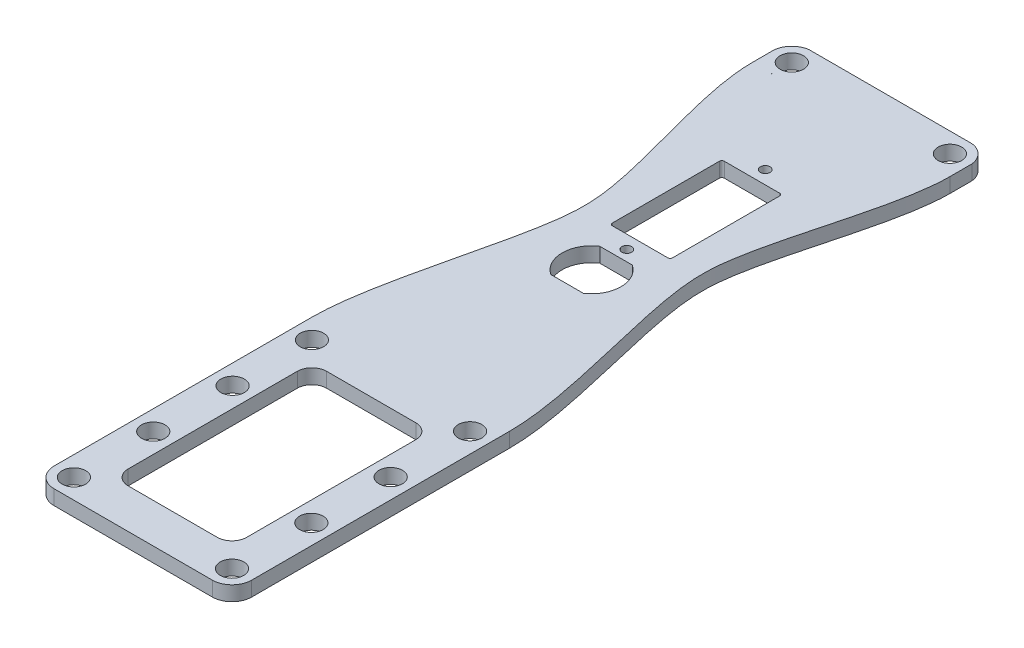
SolidWorks part; units mm, degrees
ref_plane "Front Plane" through (0, 0, 0) normal (0, 0, 1) x (1, 0, 0)
ref_plane "Top Plane" through (0, 0, 0) normal (0, 1, 0) x (1, 0, 0)
ref_plane "Right Plane" through (0, 0, 0) normal (1, 0, 0) x (0, 0, -1)
sketch "Sketch2" plane through (0, 0, 0) normal (0, 1, 0) x (1, 0, 0)
  line L4 (0.3089, 36.1371) -> (40.6689, 36.1371)
  line L5 (0.3089, 36.1371) -> (0.3089, 28.0671)
  line L6 (0.3832, -61.9329) -> (40.7432, -61.9329)
  line L11 (0.3832, -61.9329) -> (40.7432, -61.9329)
  line L12 (0.3832, -61.9329) -> (0.3832, -118.6029)
  line L13 (0.3832, -118.6029) -> (40.7432, -118.6029)
  line L14 (40.7432, -61.9329) -> (40.7432, -118.6029)
  line L15 (0.3832, -61.9329) -> (0.3832, -70.0029)
  line L17 (40.7432, -61.9329) -> (40.7432, -70.0029)
  line L18 (0.3832, -61.9329) -> (40.7432, -70.0029) construction
  line L19 (0.3832, -70.0029) -> (40.7432, -61.9329) construction
  line L21 (0.3832, -110.5329) -> (0.3832, -118.6029)
  line L22 (0.3832, -118.6029) -> (40.7432, -118.6029)
  line L23 (40.7432, -110.5329) -> (40.7432, -118.6029)
  line L24 (0.3832, -110.5329) -> (40.7432, -118.6029) construction
  line L25 (0.3832, -118.6029) -> (40.7432, -110.5329) construction
  line L26 (0.3089, 28.0671) -> (40.6689, 28.0671)
  line L27 (40.6689, 36.1371) -> (40.6689, 28.0671)
  line L28 (11.4632, -70.0029) -> (29.6632, -70.0029)
  line L29 (8.4632, -73.0029) -> (8.4632, -107.5329)
  line L30 (11.4632, -110.5329) -> (29.6632, -110.5329)
  line L31 (32.6632, -73.0029) -> (32.6632, -107.5329)
  line L32 (0.3089, 36.1371) -> (40.6689, 28.0671) construction
  line L33 (0.3089, 28.0671) -> (40.6689, 36.1371) construction
  circle A2 centre (4.3439, 32.1021) radius 2.4
  circle A3 centre (36.6339, 32.1021) radius 2.4
  circle A5 centre (4.4182, -65.9679) radius 2.4
  circle A6 centre (36.7082, -65.9679) radius 2.4
  arc A7 (4.8057, 36.1371) -> (4.8057, 28.0671) centre (4.3439, 32.1021) ccw
  arc A8 (37.0957, 28.0671) -> (37.0957, 36.1371) centre (36.6339, 32.1021) ccw
  circle A10 centre (4.4182, -114.5679) radius 2.4
  circle A11 centre (36.7082, -114.5679) radius 2.4
  arc A12 (4.3439, -110.5329) -> (4.3439, -118.6029) centre (4.4182, -114.5679) ccw
  arc A13 (36.7825, -118.6029) -> (36.6339, -110.5329) centre (36.7082, -114.5679) ccw
  circle A15 centre (4.4232, -82.1679) radius 2.4
  circle A16 centre (4.4232, -98.3679) radius 2.4
  circle A17 centre (36.7032, -98.3679) radius 2.4
  circle A18 centre (36.7032, -82.1679) radius 2.4
  arc A19 (29.6632, -110.5329) -> (32.6632, -107.5329) centre (29.6632, -107.5329) ccw
  arc A20 (8.4632, -107.5329) -> (11.4632, -110.5329) centre (11.4632, -107.5329) ccw
  arc A21 (29.6632, -70.0029) -> (32.6632, -73.0029) centre (29.6632, -73.0029) cw
  arc A22 (11.4632, -70.0029) -> (8.4632, -73.0029) centre (11.4632, -73.0029) ccw
  spline S0 degree 3 poles (0.3832, -61.9329) (0.3832, -49.5533) (8.5933, -25.5683) (8.563, -3.223) (0.3089, 17.1634) (0.3089, 28.0671) knots 0 0 0 0 0.447163 0.547163 1 1 1 1
  spline S1 degree 3 poles (40.7432, -61.9329) (40.7432, -49.5533) (32.5265, -25.5683) (32.5713, -3.223) (40.6689, 17.1634) (40.6689, 28.0671) knots 0 0 0 0 0.447163 0.547163 1 1 1 1
  point P0 (20.4889, 32.1021)
  point P19 (20.5632, -65.9679)
  point P29 (0.3089, 28.164)
  point P33 (20.5632, -114.5679)
  point P59 (32.6632, -110.5329)
  point P66 (8.4632, -70.0029)
  dimension "D13" = 4.8
  dimension "D14" = 4.8
  dimension "D22" = 4.8
  dimension "D23" = 4.8
  dimension "D33" = 3
  dimension "D8" = 4.8
  dimension "D9" = 4.8
  dimension "D11" = 40.36
  dimension "D12" = 8.07
  dimension "D15" = 4.035
  dimension "D16" = 4.035
  dimension "D17" = 4.035
  dimension "D18" = 4.035
  dimension "D20" = 32.29
  dimension "D21" = 8.07
  dimension "D25" = 4.035
  dimension "D27" = 4.035
  dimension "D29" = 32.29
  dimension "D28" = 16.2
  dimension "D30" = 16.2
  dimension "D31" = 16.2
  dimension "D19" = 4.04
  dimension "D32" = 4.04
  dimension "D35" = 4.04
  dimension "D36" = 4.04
  dimension "D4" = 90
  dimension "D5" = 90
  dimension "D6" = 40.36
  dimension "D7" = 8.07
  dimension "D10" = 4.035
  dimension "D24" = 4.035
  dimension "D26" = 4.035
  dimension "D34" = 4.035
  dimension "D37" = 32.29
extrude "Boss-Extrude1" add sketch "Sketch2" along normal blind 3
sketch "Sketch3" plane through (0, 3, 0) normal (0, 1, 0) x (1, 0, 0)
  line L0 (14.9132, -15.1029) -> (26.2132, -15.1029)
  line L1 (14.4132, -14.6029) -> (14.4132, 7.2471)
  line L2 (14.9132, 7.7471) -> (26.2132, 7.7471)
  line L3 (26.7132, -14.6029) -> (26.7132, 7.2471)
  line L4 (14.4132, -15.1029) -> (26.7132, 7.7471) construction
  line L5 (14.4132, 7.7471) -> (26.7132, -15.1029) construction
  line L6 (20.5632, 17.1857) -> (20.5632, -26.7801) construction
  line L7 (15.1132, -19.8029) -> (26.0132, -19.8029)
  line L8 (14.6132, -19.3029) -> (14.6132, 11.9471)
  line L9 (15.1132, 12.4471) -> (26.0132, 12.4471)
  line L10 (26.5132, -19.3029) -> (26.5132, 11.9471)
  line L11 (14.6132, -19.8029) -> (26.5132, 12.4471) construction
  line L12 (14.6132, 12.4471) -> (26.5132, -19.8029) construction
  line L15 (-6.1466, -3.6779) -> (20.1802, -3.6779) construction
  line L18 (11.4632, -70.0029) -> (29.6632, -70.0029) construction
  line L19 (0.3832, -61.9329) -> (0.3832, -114.6422) construction
  line L20 (40.7432, -61.9329) -> (40.7432, -114.6422) construction
  arc A0 (14.9132, -15.1029) -> (14.4132, -14.6029) centre (14.9132, -14.6029) cw
  arc A1 (26.2132, -15.1029) -> (26.7132, -14.6029) centre (26.2132, -14.6029) ccw
  arc A2 (26.2132, 7.7471) -> (26.7132, 7.2471) centre (26.2132, 7.2471) cw
  arc A3 (14.4132, 7.2471) -> (14.9132, 7.7471) centre (14.9132, 7.2471) cw
  arc A4 (20.0632, 11.3131) -> (21.0632, 11.3131) centre (20.5632, 10.4471) ccw
  arc A5 (20.0632, -18.669) -> (21.0632, -18.669) centre (20.5632, -17.8029) cw
  arc A6 (26.0132, -19.8029) -> (26.5132, -19.3029) centre (26.0132, -19.3029) ccw
  arc A7 (15.1132, -19.8029) -> (14.6132, -19.3029) centre (15.1132, -19.3029) cw
  arc A8 (14.6132, 11.9471) -> (15.1132, 12.4471) centre (15.1132, 11.9471) cw
  arc A9 (26.0132, 12.4471) -> (26.5132, 11.9471) centre (26.0132, 11.9471) cw
  circle A10 centre (20.5632, -17.8029) radius 1
  circle A11 centre (20.5632, 10.4471) radius 1
  point P0 (20.5632, -3.6779)
  point P17 (20.5632, -3.6779)
  dimension "D3" = 0.5
  dimension "D7" = 1
  dimension "D9" = 0.5
  dimension "D1" = 22.85
  dimension "D2" = 12.3
  dimension "D4" = 11.9
  dimension "D5" = 32.25
  dimension "D8" = 2
  dimension "D10" = 50.2
  dimension "D11" = 20.18
  dimension "D12" = 40.36
extrude "Cut-Extrude1" cut sketch "Sketch3" against normal blind 10 contours A5 A10 | A4 A11 | L1 A3 L2 A2 L3 A1 L0 A0
sketch "Sketch4" plane through (0, 3, 0) normal (0, 1, 0) x (1, 0, 0)
  line L0 (11.4632, -70.0029) -> (29.6632, -70.0029) construction
  line L1 (23.8798, -30.0029) -> (17.2466, -30.0029)
  line L2 (23.8798, -30.0029) -> (23.8798, -20.0029)
  line L3 (23.8798, -20.0029) -> (17.2466, -20.0029)
  line L4 (17.2466, -30.0029) -> (17.2466, -20.0029)
  line L5 (23.8798, -30.0029) -> (17.2466, -20.0029) construction
  line L6 (23.8798, -20.0029) -> (17.2466, -30.0029) construction
  line L7 (40.7432, -61.9329) -> (40.7432, -114.6422) construction
  line L8 (0.3832, -61.9329) -> (0.3832, -114.6422) construction
  circle A0 centre (20.5632, -25.0029) radius 6
  point P8 (20.5632, -70.0029)
  dimension "D1" = 12
  dimension "D3" = 45
  dimension "D4" = 20.18
  dimension "D5" = 40.36
  dimension "D2" = 10
extrude "Cut-Extrude2" cut sketch "Sketch4" against normal blind 10 contours L4 L1 L2 L3 | L2 A0 | L4 A0
equation "\"D30@Sketch2\"=\"D28@Sketch2\""
equation "\"D31@Sketch2\"=\"D28@Sketch2\""
equation "\"D11@Sketch3\"=\"D12@Sketch3\"/2"
equation "\"D4@Sketch4\"=\"D5@Sketch4\"/2"
